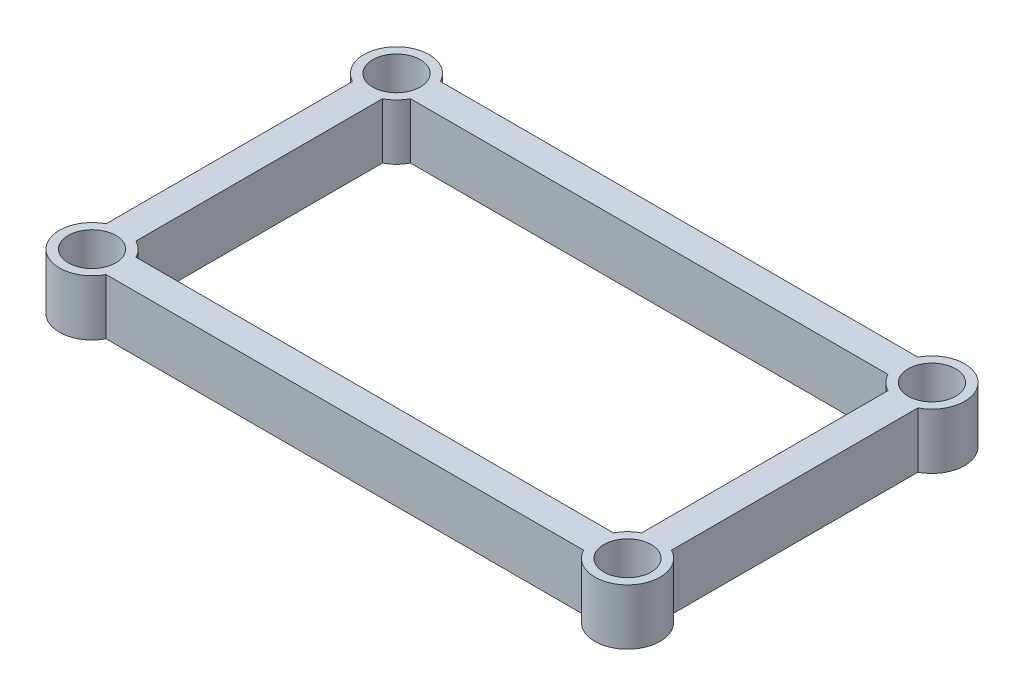
SolidWorks part; units mm, degrees
material "Gray Cast Iron"
ref_plane "Front Plane" through (0, 0, 0) normal (0, 0, 1) x (1, 0, 0)
ref_plane "Top Plane" through (0, 0, 0) normal (0, 1, 0) x (1, 0, 0)
ref_plane "Right Plane" through (0, 0, 0) normal (1, 0, 0) x (0, 0, -1)
sketch "Sketch1" plane through (0, 0, 0) normal (0, 1, 0) x (1, 0, 0)
  line L0 (-208, -123) -> (208, -123)
  line L1 (208, -123) -> (208, 123)
  line L2 (208, 123) -> (-208, 123)
  line L3 (-208, 123) -> (-208, -123)
  dimension "D1" = 416
  dimension "D2" = 246
  dimension "D3" = 208
  dimension "D4" = 123
extrude "Boss-Extrude1" add sketch "Sketch1" along normal mid plane 41
sketch "Sketch2" plane through (0, 0, 0) normal (0, 1, 0) x (1, 0, 0)
  line L0 (-186, -101) -> (186, -101)
  line L1 (186, -101) -> (186, 101)
  line L2 (186, 101) -> (-186, 101)
  line L3 (-186, 101) -> (-186, -101)
  dimension "D1" = 372
  dimension "D2" = 202
  dimension "D3" = 186
  dimension "D4" = 101
extrude "Cut-Extrude1" cut sketch "Sketch2" against normal mid plane 60
sketch "Sketch3" plane through (0, 0, 0) normal (0, 1, 0) x (1, 0, 0)
  circle A0 centre (-197, -112) radius 24
  circle A1 centre (-197, 112) radius 24
  circle A2 centre (197, -112) radius 24
  circle A3 centre (197, 112) radius 24
  dimension "D3" = 48
  dimension "D6" = 48
  dimension "D9" = 48
  dimension "D12" = 48
  dimension "D1" = 197
  dimension "D2" = 112
  dimension "D4" = 197
  dimension "D5" = 112
  dimension "D7" = 197
  dimension "D8" = 112
  dimension "D10" = 197
  dimension "D11" = 112
extrude "Boss-Extrude2" add sketch "Sketch3" along normal mid plane 41
sketch "Sketch4" plane through (0, 0, 0) normal (0, 1, 0) x (1, 0, 0)
  circle A0 centre (-197, -112) radius 17.5
  circle A1 centre (-197, 112) radius 17.5
  circle A2 centre (197, -112) radius 17.5
  circle A3 centre (197, 112) radius 17.5
  dimension "D3" = 35
  dimension "D6" = 35
  dimension "D9" = 35
  dimension "D12" = 35
  dimension "D1" = 197
  dimension "D2" = 112
  dimension "D4" = 197
  dimension "D5" = 112
  dimension "D7" = 197
  dimension "D8" = 112
  dimension "D10" = 197
  dimension "D11" = 112
extrude "Cut-Extrude2" cut sketch "Sketch4" against normal mid plane 60
